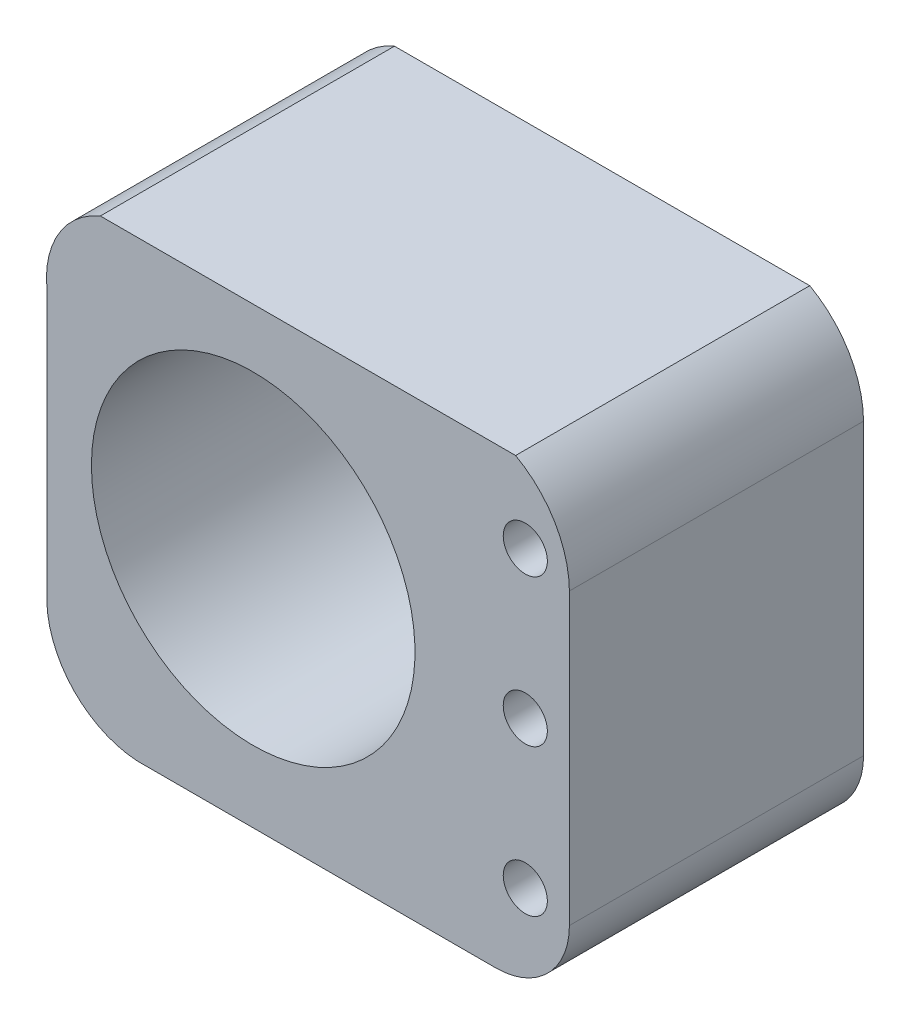
SolidWorks part; units mm, degrees
ref_plane "Alzado" through (0, 0, 0) normal (0, 0, 1) x (1, 0, 0)
ref_plane "Planta" through (0, 0, 0) normal (0, 1, 0) x (1, 0, 0)
ref_plane "Vista lateral" through (0, 0, 0) normal (1, 0, 0) x (0, 0, -1)
sketch "Croquis1" plane through (0, 0, 0) normal (0, 0, 1) x (1, 0, 0)
  line L13 (19.9349, -13.245) -> (44.3651, -13.245)
  line L15 (17.4709, 17.5894) -> (45.7084, 17.605)
  line L16 (49.3651, 11.455) -> (49.3651, -8.245)
  line L17 (13.8426, 11.455) -> (13.8426, -6.245)
  circle A5 centre (27.8651, 2.605) radius 11
  circle A10 centre (46.3651, 2.455) radius 1.5
  circle A11 centre (46.3651, 12.455) radius 1.5
  circle A12 centre (46.3651, -7.545) radius 1.5
  arc A14 (13.8426, -6.245) -> (19.9349, -13.245) centre (20.3888, -6.6989) ccw
  arc A15 (13.8426, 11.455) -> (17.4709, 17.5894) centre (19.7417, 12.1061) cw
  arc A17 (45.7084, 17.605) -> (49.3651, 11.455) centre (42.2411, 11.3812) cw
  arc A18 (49.3651, -8.245) -> (44.3651, -13.245) centre (44.3651, -8.245) cw
extrude "Saliente-Extruir1" add sketch "Croquis1" along normal blind 20
